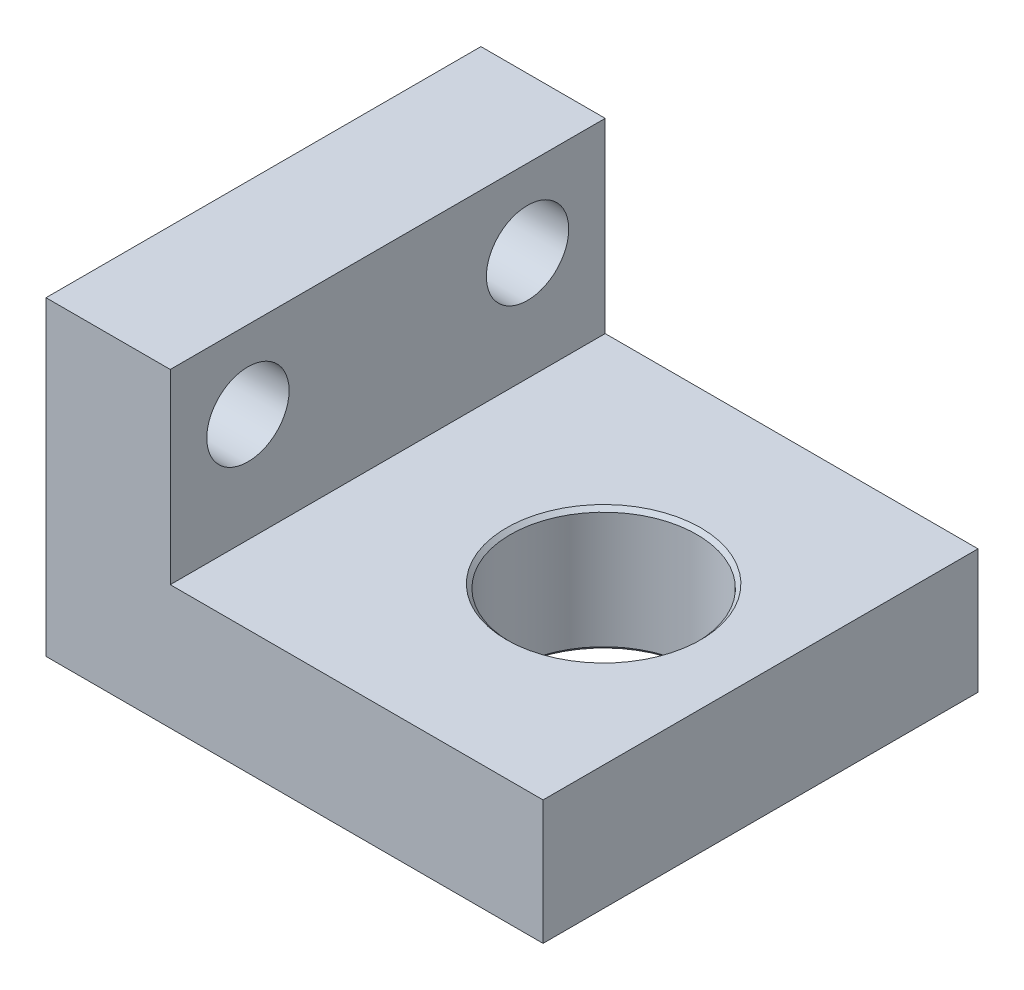
SolidWorks part; units mm, degrees
material "AISI 1045 Steel, cold drawn"
ref_plane "Front Plane" through (0, 0, 0) normal (0, 0, 1) x (1, 0, 0)
ref_plane "Top Plane" through (0, 0, 0) normal (0, 1, 0) x (1, 0, 0)
ref_plane "Right Plane" through (0, 0, 0) normal (1, 0, 0) x (0, 0, -1)
sketch "Sketch1" plane through (0, 0, 0) normal (0, 1, 0) x (1, 0, 0)
  line L1 (10.1, -14) -> (-21.9, -14)
  line L2 (10.1, -14) -> (10.1, 14)
  line L3 (10.1, 14) -> (-21.9, 14)
  line L4 (-21.9, -14) -> (-21.9, 14)
  line L5 (10.1, -14) -> (-21.9, 14) construction
  line L6 (10.1, 14) -> (-21.9, -14) construction
  circle A1 centre (0, 0) radius 6 construction
  point P2 (-5.9, 0)
  point P8 (0, 0)
  dimension "D1" = 12
  dimension "D2" = 21.9
  dimension "D3" = 28
  dimension "D4" = 32
extrude "Boss-Extrude1" add sketch "Sketch1" along normal blind 8
hole_wizard "Ø12.0 (12) Diameter Hole1" positions "Sketch2" profile "Sketch3" hole size "Ø12.0" standard "ANSI Metric" end condition through all
sketch "Sketch2" plane through (0, 8, 0) normal (0, 1, 0) x (1, 0, 0)
  point P0 (0, 0)
sketch "Sketch3" plane through (0, 8, 0) normal (1, 0, 0) x (0, 0, 1)
  line L0 (0, 0) -> (0, 8)
  line L1 (0, 8) -> (6.25, 8)
  line L2 (6, 7.75) -> (6, 0.25)
  line L3 (6, 0.25) -> (6.25, 0)
  line L5 (6.25, 0) -> (0, 0)
  line L6 (-6, 0.25) -> (-6.25, 0) construction
  line L7 (6.25, 8) -> (6, 7.75)
  line L8 (-6.25, 8) -> (-6, 7.75) construction
  line L11 (0, -6.35) -> (0, 107.95) construction
  dimension "Thru Hole Dia." = 12
  dimension "Thru Hole Depth" = 8
  dimension "Near C'Sink Dia." = 12.5
  dimension "Near C'Sink Angle" = 90
  dimension "Far C'Sink Dia." = 12.5
  dimension "Far C'Sink Angle" = 90
sketch "Sketch4" plane through (-21.9, 0, 0) normal (-1, 0, 0) x (0, 0, 1)
  line L1 (-14, 0) -> (14, 0)
  line L2 (-14, 0) -> (-14, 20)
  line L3 (-14, 20) -> (14, 20)
  line L4 (14, 0) -> (14, 20)
  point P5 (14, 0)
  dimension "D1" = 20
extrude "Boss-Extrude2" add sketch "Sketch4" against normal blind 8
hole_wizard "M5 Clearance Hole1" positions "Sketch5" profile "Sketch7" hole size "M5" standard "ANSI Metric" end condition through all
sketch "Sketch5" plane through (-13.9, 0, 0) normal (1, 0, 0) x (0, 0, -1)
  line L0 (-9, 15) -> (9, 15) construction
  line L2 (-14, 20) -> (14, 20) construction
  point P0 (-9, 15)
  point P2 (9, 15)
  point P9 (0, 15)
  dimension "D1" = 18
  dimension "D2" = 5
sketch "Sketch7" plane through (-13.9, 15, 9) normal (0, 1, 0) x (0, 0, -1)
  line L0 (0, 0) -> (0, 8)
  line L1 (0, 8) -> (2.65, 8)
  line L2 (2.65, 8) -> (2.65, 0)
  line L5 (2.65, 0) -> (0, 0)
  line L11 (0, -6.35) -> (0, 107.95) construction
  dimension "Thru Hole Dia." = 5.3
  dimension "Thru Hole Depth" = 8
